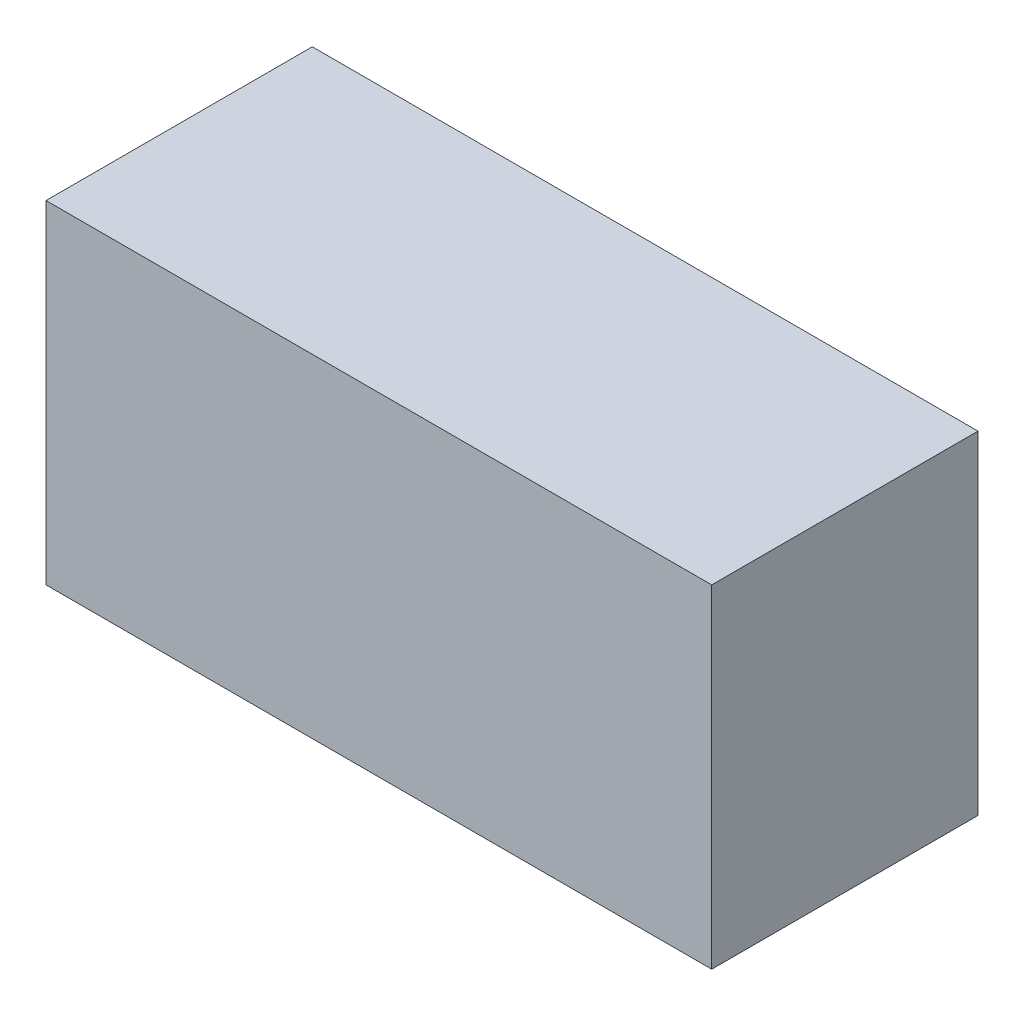
SolidWorks part; units mm, degrees
ref_plane "Plano frontal" through (0, 0, 0) normal (0, 0, 1) x (1, 0, 0)
ref_plane "Plano superior" through (0, 0, 0) normal (0, 1, 0) x (1, 0, 0)
ref_plane "Plano direito" through (0, 0, 0) normal (1, 0, 0) x (0, 0, -1)
sketch "Esboço1" plane through (0, 0, 0) normal (0, 0, 1) x (1, 0, 0)
  line L1 (-100, 50) -> (100, 50)
  line L2 (-100, 50) -> (-100, -50)
  line L3 (-100, -50) -> (100, -50)
  line L4 (100, 50) -> (100, -50)
  line L5 (-100, 50) -> (100, -50) construction
  line L6 (-100, -50) -> (100, 50) construction
  point P0 (0, 0)
  dimension "D1" = 100
  dimension "D2" = 200
extrude "Ressalto-extrusão1" add sketch "Esboço1" along normal blind 80
sketch "Esboço2" plane through (0, 0, 0) normal (0, 0, -1) x (-1, 0, 0)
  line L0 (-100, 50) -> (100, 50) construction
  line L1 (-95, 45) -> (95, 45)
  line L2 (-95, 45) -> (-95, -45)
  line L3 (-95, -45) -> (95, -45)
  line L4 (95, 45) -> (95, -45)
  line L5 (-95, 45) -> (95, -45) construction
  line L6 (-95, -45) -> (95, 45) construction
  line L7 (-100, -50) -> (-100, 50) construction
  point P0 (0, 0)
  dimension "D1" = 5
  dimension "D2" = 5
extrude "Corte-extrusão1" cut sketch "Esboço2" against normal blind 75
